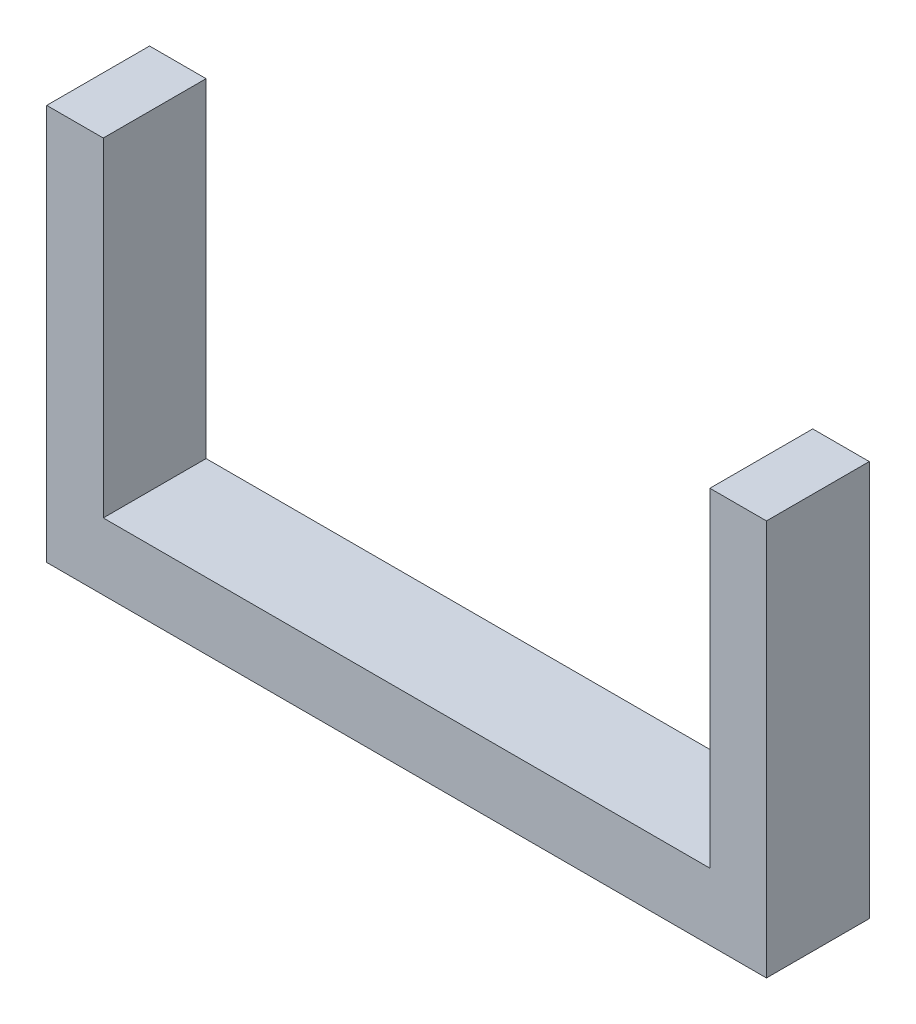
SolidWorks part; units mm, degrees
ref_plane "Front Plane" through (0, 0, 0) normal (0, 0, 1) x (1, 0, 0)
ref_plane "Top Plane" through (0, 0, 0) normal (0, 1, 0) x (1, 0, 0)
ref_plane "Right Plane" through (0, 0, 0) normal (1, 0, 0) x (0, 0, -1)
other "Configuration Table"
sketch "Sketch2" plane through (0, 0, 0) normal (0, 0, 1) x (1, 0, 0)
  line L1 (-14, -9) -> (14, -9)
  line L2 (-14, -9) -> (-14, 9)
  line L3 (-14, 9) -> (14, 9)
  line L4 (14, -9) -> (14, 9)
  line L5 (-11.8, -6.4) -> (11.8, -6.4)
  line L6 (-11.8, -6.4) -> (-11.8, 6.4)
  line L7 (-11.8, 6.4) -> (11.8, 6.4)
  line L8 (11.8, -6.4) -> (11.8, 6.4)
extrude "Servo_mount_cradle" add sketch "Sketch2" along normal blind 4 from offset 0
sketch "Sketch3" plane through (0, 0, 0) normal (0, 0, 1) x (1, 0, 0)
  line L1 (-20, 6.4) -> (20, 6.4)
  line L2 (-20, 6.4) -> (-20, 16.4)
  line L3 (-20, 16.4) -> (20, 16.4)
  line L4 (20, 6.4) -> (20, 16.4)
extrude "Rear_wall_clearance_U_bracket" cut sketch "Sketch3" along normal through all
